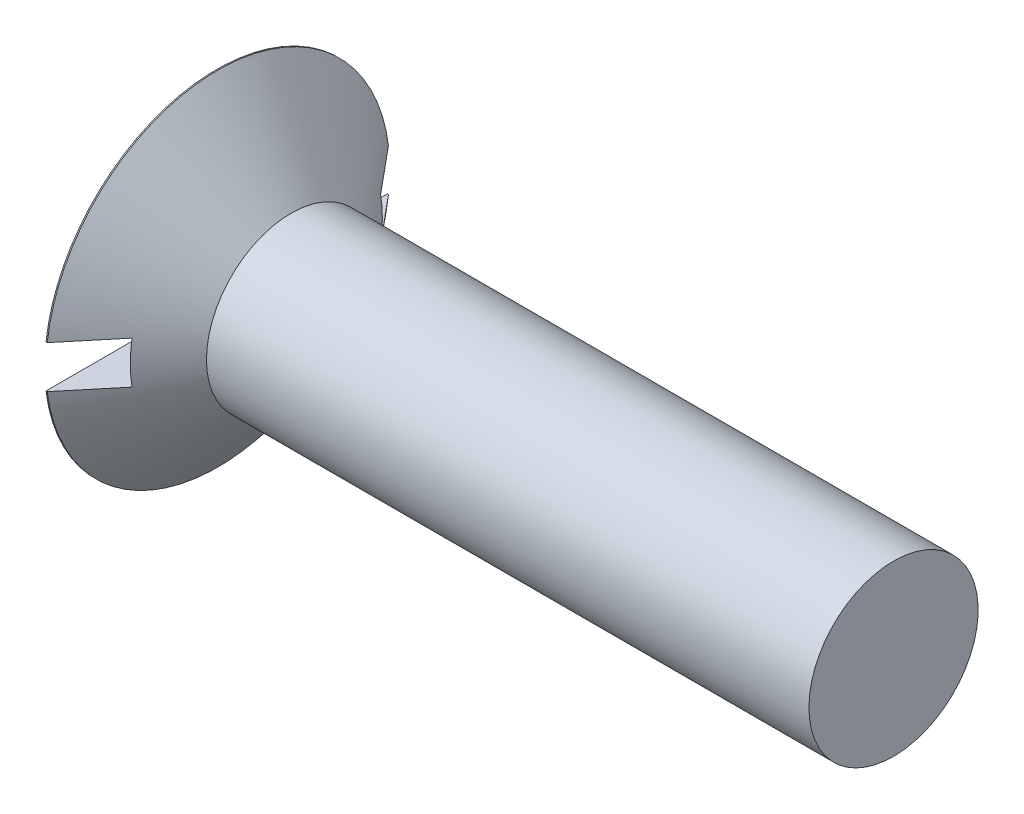
SolidWorks part; units mm, degrees
revolve "Base-Revolve" add sketch "BodySke" angle 360 about L5
sketch "BodySke" plane through (0, 0, 0) normal (0, 0, 1) x (1, 0, 0)
  line L0 (0, 0) -> (0, 9.6774)
  line L1 (0, 9.6774) -> (0.0669, 9.6774)
  line L2 (4.191, 4.7625) -> (38.1, 4.7625)
  line L3 (38.1, 4.7625) -> (38.1, 0)
  line L4 (38.1, 0) -> (0, 0)
  line L5 (-6.35, 0) -> (82.55, 0) construction
  line L6 (4.191, -4.7625) -> (38.1, -4.7625) construction
  line L7 (0.0669, -9.6774) -> (4.191, -4.7625) construction
  line L8 (0.0669, 9.6774) -> (4.191, 4.7625)
  line L9 (0, -9.6774) -> (0.0669, -9.6774) construction
  line L10 (5.7785, 6.35) -> (5.7785, -3.175) construction
  line L11 (6.35, 6.35) -> (6.35, -3.175) construction
  dimension "Head_ang" = 100
  dimension "Diameter" = 4.826
cosmetic thread "ThreadCosmetic" [suppressed] parameters "Thread_length"=3.5001, "Thread_minor"=7.9248
extrude "Slot" cut sketch "Sketch2" against normal blind 2.2352
sketch "Sketch2" plane through (0, 0, 0) normal (-1, 0, 0) x (0, 0, 1)
  line L0 (-9.6774, -1.1938) -> (9.6774, -1.1938)
  line L1 (-9.6774, -1.1938) -> (-9.6774, 1.1938)
  line L2 (9.6774, 1.1938) -> (-9.6774, 1.1938)
  line L3 (9.6774, 1.1938) -> (9.6774, -1.1938)
  dimension "D1" = 0.762
  dimension "D2" = 8.4582
  dimension "D3" = 4.2291
ref_plane "Plane1" through (0, 0, 0) normal (0, 0, 1) x (1, 0, 0)
ref_plane "Plane2" through (0, 0, 0) normal (0, 1, 0) x (1, 0, 0)
ref_plane "Plane3" through (0, 0, 0) normal (1, 0, 0) x (0, 0, -1)
other "Configuration Table"
sketch "Sketch3" plane through (0, 0, 0) normal (-1, 0, 0) x (0, 0, 1)
  line L0 (-1.0922, 6.6421) -> (1.0922, 6.6421)
  line L1 (1.0922, 6.6421) -> (1.0922, -6.6421)
  line L2 (1.0922, -6.6421) -> (-1.0922, -6.6421)
  line L3 (-1.0922, -6.6421) -> (-1.0922, 6.6421)
  dimension "D1" = 2.8575
  dimension "D2" = 0.5334
ref_plane "Plane4" through (7.9756, 0, 0) normal (-1, 0, 0) x (0, 0, 1)
sketch "Sketch4" plane through (7.9756, 0, 0) normal (-1, 0, 0) x (0, 0, 1)
  line L0 (-0.5461, 0.5461) -> (0.5461, 0.5461)
  line L3 (0.5461, 0.5461) -> (0.5461, -0.5461)
  line L4 (0.5461, -0.5461) -> (-0.5461, -0.5461)
  line L5 (-0.5461, -0.5461) -> (-0.5461, 0.5461)
  dimension "D2" = 0.5334
  dimension "D1" = 0.5334
  dimension "D3" = 0.2667
  dimension "D4" = 0.2667
loft "Cross" cut profiles "Sketch3", "Sketch4"
pattern_circular "CirPattern1" count 2 every 90 about axis through (0, 0, 0) along (1, 0, 0) of "Cross"
sketch "ThdSchSke" plane through (0, 0, 0) normal (0, 0, 1) x (1, 0, 0)
  line L0 (6.35, -3.9624) -> (5.7898, -4.7625)
  line L1 (6.35, -3.9624) -> (6.9103, -4.7625)
  line L2 (6.9103, -4.7625) -> (6.9103, -5.9531)
  line L3 (-3.175, 0) -> (5.1513, 0) construction
  line L5 (6.9103, -5.9531) -> (5.7898, -5.9531)
  line L6 (5.7898, -5.9531) -> (5.7898, -4.7625)
  line L7 (0, 9.6774) -> (0, 1.1938) construction
  dimension "Thread_minor" = 3.8811
  dimension "Diameter" = 4.826
  dimension "Start" = 2.8499
revolve "ThreadSchematic" [suppressed] cut sketch "ThdSchSke" angle 360 about L3
pattern_linear "ThdSchPat" [suppressed]
equation "\"D1@Sketch3\" = \"Cross_dia@Sketch3\" / 2"
equation "\"D2@Sketch3\" = \"Cross_width@Sketch3\" / 2"
equation "\"D1@Sketch4\" = \"Cross_width@Sketch3\" *.5"
equation "\"D2@Sketch4\" = \"D1@Sketch4\""
equation "\"D4@Sketch4\" = \"D2@Sketch4\" / 2"
equation "\"D3@Sketch4\" = \"D1@Sketch4\" / 2"
equation "\"D1@Sketch2\" = \"Slot_width@Sketch2\" / 2"
equation "\"D2@Sketch2\" = \"Head_dia@BodySke\""
equation "\"D3@Sketch2\" = \"D2@Sketch2\" / 2"
equation "\"Thread_length@ThreadCosmetic\" = ((sgn( (\"Length@BodySke\" - \"Advance@BodySke\" - \"Head_ht@BodySke\" ) - \"Thread_nom@BodySke\" )-1)*( (\"Length@BodySke\" - \"Advance@BodySke\" - \"Head_ht@BodySke\" ) - \"Thread_nom@BodySke\" ))/-2+ \"Thread_nom@BodySke\""
equation "\"Thread_minor@ThdSchSke\" = \"Thread_minor@ThreadCosmetic\""
equation "\"Diameter@ThdSchSke\" = \"Diameter@BodySke\""
equation "\"Overcut@ThdSchSke\" = \"Diameter@BodySke\" * 1.25"
equation "\"Start@ThdSchSke\" = 0.000001 + \"Length@BodySke\" - \"Thread_length@ThreadCosmetic\"  '---Countersunk---"
equation "\"Num_threads@ThdSchPat\" = int( \"Thread_length@ThreadCosmetic\" / \"Advance@BodySke\" + 0.999 )  + 1"
equation "\"Advance@ThdSchPat\" = \"Thread_length@ThreadCosmetic\" /  (\"Num_threads@ThdSchPat\" - 1) 'relax it"
